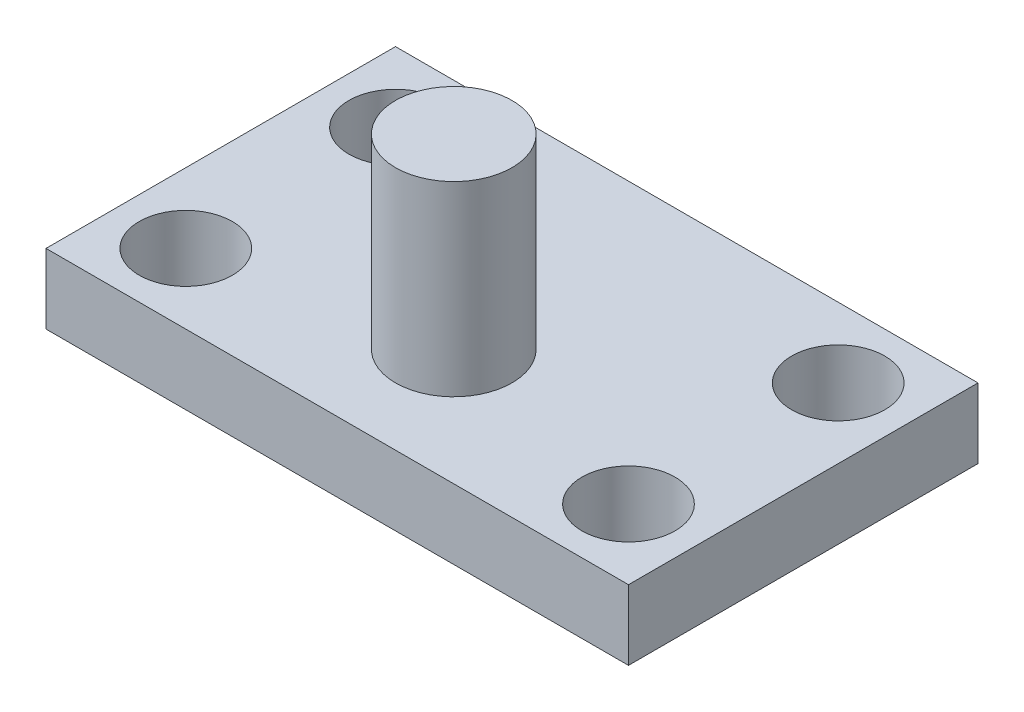
SolidWorks part; units mm, degrees
ref_plane "Front Plane" through (0, 0, 0) normal (0, 0, 1) x (1, 0, 0)
ref_plane "Top Plane" through (0, 0, 0) normal (0, 1, 0) x (1, 0, 0)
ref_plane "Right Plane" through (0, 0, 0) normal (1, 0, 0) x (0, 0, -1)
sketch "Sketch1" plane through (0, 0, 0) normal (0, 1, 0) x (1, 0, 0)
  line L0 (-136.0465, 0) -> (142.4419, 0) construction
  line L1 (-125, 75) -> (125, 75)
  line L2 (-125, 75) -> (-125, -75)
  line L3 (-125, -75) -> (125, -75)
  line L4 (125, 75) -> (125, -75)
  line L7 (0, 105.5233) -> (0, -91.5698) construction
  circle A0 centre (-95, 45) radius 20
  circle A1 centre (-95, -45) radius 20
  circle A2 centre (95, -45) radius 20
  circle A3 centre (95, 45) radius 20
  point P0 (0, 0)
  dimension "D3" = 190
  dimension "D4" = 40
  dimension "D1" = 250
  dimension "D2" = 150
  dimension "D6" = 30
  dimension "D7" = 30
extrude "Boss-Extrude1" add sketch "Sketch1" along normal blind 30
sketch "Sketch2" plane through (0, 30, 0) normal (0, 1, 0) x (1, 0, 0)
  line L0 (0, 0) -> (0, -77.6047) construction
  line L1 (125, 75) -> (-125, 75) construction
  circle A0 centre (0, -25) radius 25
  dimension "D1" = 50
  dimension "D2" = 100
extrude "Boss-Extrude2" add sketch "Sketch2" along normal blind 80
